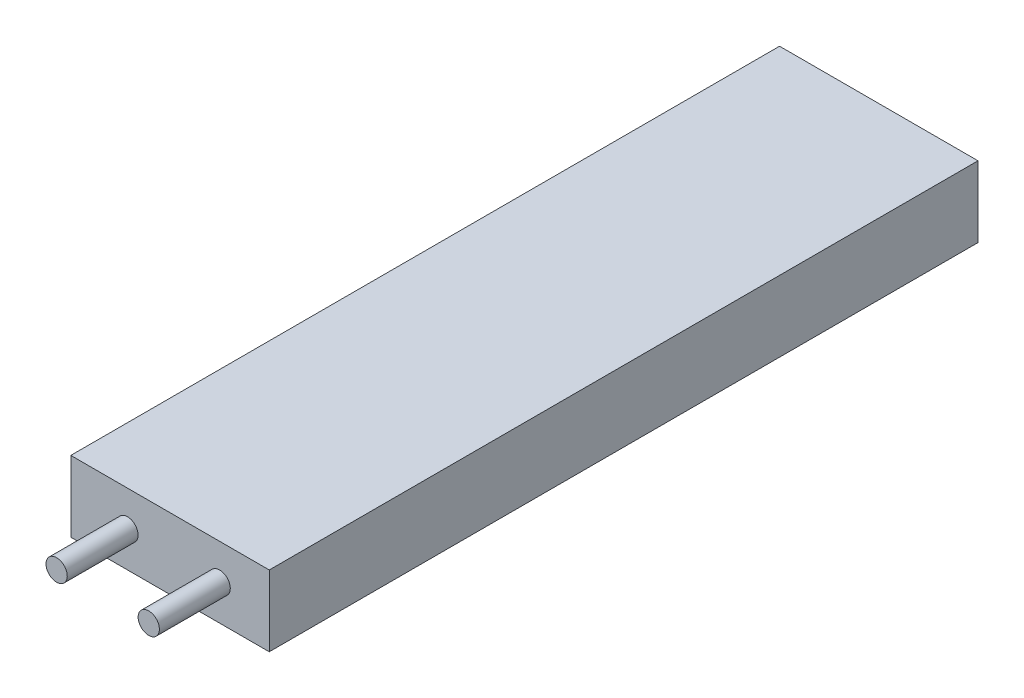
SolidWorks part; units mm, degrees
ref_plane "Front Plane" through (0, 0, 0) normal (0, 0, 1) x (1, 0, 0)
ref_plane "Top Plane" through (0, 0, 0) normal (0, 1, 0) x (1, 0, 0)
ref_plane "Right Plane" through (0, 0, 0) normal (1, 0, 0) x (0, 0, -1)
sketch "Sketch1" plane through (0, 0, 0) normal (0, 1, 0) x (1, 0, 0)
  line L1 (-7, -25) -> (7, -25)
  line L2 (-7, -25) -> (-7, 25)
  line L3 (-7, 25) -> (7, 25)
  line L4 (7, -25) -> (7, 25)
  line L5 (-7, -25) -> (7, 25) construction
  line L6 (-7, 25) -> (7, -25) construction
  point P0 (0, 0)
  dimension "D1" = 14
  dimension "D2" = 50
extrude "Boss-Extrude1" add sketch "Sketch1" along normal blind 5 contours L2 L3 L4 L1
sketch "Sketch2" plane through (0, 0, 25) normal (0, 0, 1) x (1, 0, 0)
  line L0 (-7, 5) -> (-7, 0) construction
  line L1 (-7, 5) -> (7, 5) construction
  circle A0 centre (-3, 2.5) radius 0.75
  circle A1 centre (3.5, 2.5) radius 0.75
  point P8 (3.4658, 2.3338)
  dimension "D2" = 1.5
  dimension "D3" = 4
  dimension "D1" = 6.5
  dimension "D4" = 2.5
extrude "Boss-Extrude2" add sketch "Sketch2" along normal blind 5
